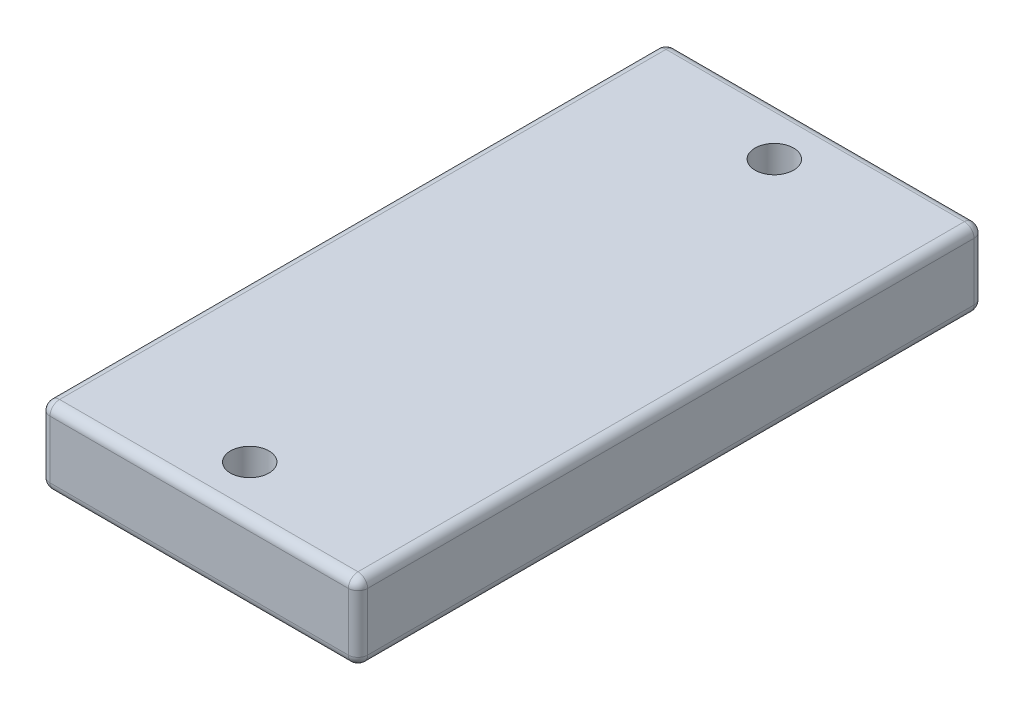
SolidWorks part; units mm, degrees
material "AISI 1035 Acero (SS)"
ref_plane "Alzado" through (0, 0, 0) normal (0, 0, 1) x (1, 0, 0)
ref_plane "Planta" through (0, 0, 0) normal (0, 1, 0) x (1, 0, 0)
ref_plane "Vista lateral" through (0, 0, 0) normal (1, 0, 0) x (0, 0, -1)
sketch "Croquis1" plane through (0, 0, 0) normal (0, 1, 0) x (1, 0, 0)
  line L1 (0, 0) -> (33, 0)
  line L2 (0, 0) -> (0, 65)
  line L3 (0, 65) -> (33, 65)
  line L4 (33, 0) -> (33, 65)
  dimension "D1" = 65
  dimension "D2" = 33
extrude "Saliente-Extruir1" add sketch "Croquis1" along normal blind 8
fillet "Redondeo1" radius 1 12 edges at (0, 4, -65) (33, 4, -65) (0, 4, 0) (33, 4, 0) (16.5, 0, 0) (33, 0, -32.5) (16.5, 0, -65) (0, 0, -32.5) (16.5, 8, -65) (33, 8, -32.5) (16.5, 8, 0) (0, 8, -32.5)
sketch "Croquis2" plane through (0, 8, 0) normal (0, 1, 0) x (1, 0, 0)
  circle A0 centre (16.5, 5.25) radius 2 construction
  circle A1 centre (16.5, 59.75) radius 2 construction
  circle A2 centre (16.5, 5.25) radius 2
  circle A3 centre (16.5, 59.75) radius 2
extrude "Cortar-Extruir1" cut sketch "Croquis2" against normal through all
